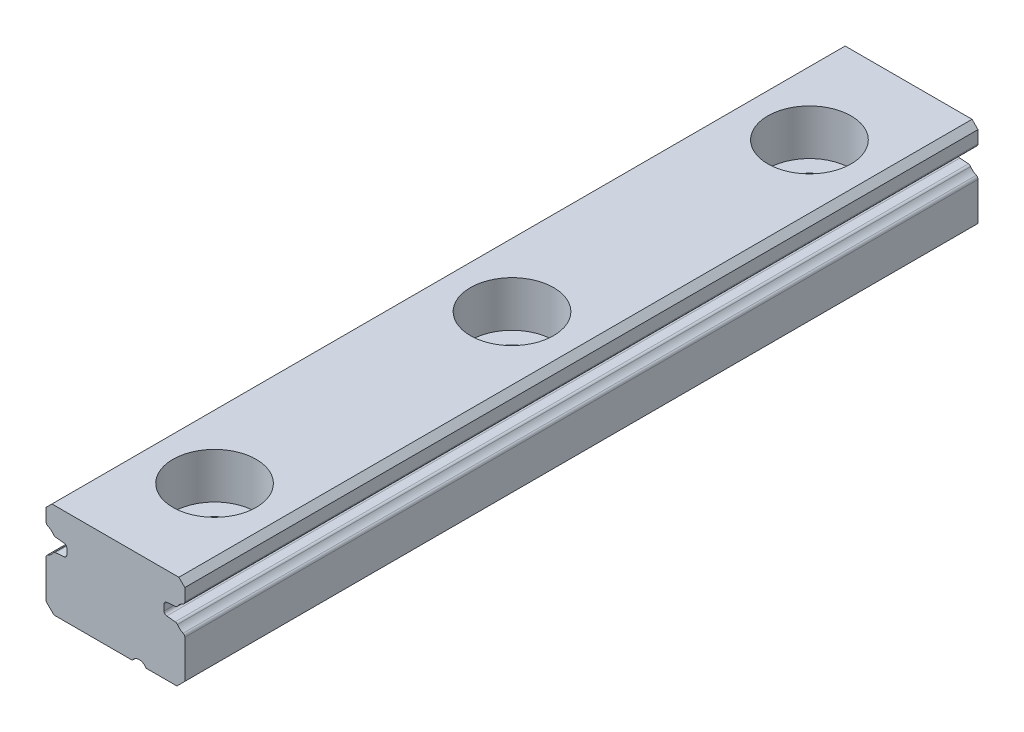
SolidWorks part; units mm, degrees
ref_plane "Front Plane" through (0, 0, 0) normal (0, 0, 1) x (1, 0, 0)
ref_plane "Top Plane" through (0, 0, 0) normal (0, 1, 0) x (1, 0, 0)
ref_plane "Right Plane" through (0, 0, 0) normal (1, 0, 0) x (0, 0, -1)
sketch "Sketch1" plane through (0, 0, 0) normal (0, 0, 1) x (1, 0, 0)
  line L0 (-3.5, 0) -> (3.5, 0) construction
  line L1 (0, -2.4) -> (0, 2.4) construction
  line L2 (0, 2.4) -> (0, -2.4) construction
  line L3 (-2.1, 2.4) -> (2.1, 2.4) construction
  line L4 (-1.2, 0.1) -> (1.2, 0.1) construction
  point P0 (0, 0.1)
  point P3 (-3.5, -2.4)
  point P4 (0, 0)
  point P8 (0, 0)
  point P11 (0, 2.4)
  point P15 (0, 2.4)
  point P17 (0, 0.1)
  point P18 (3.5, 2.4)
  point P20 (-3.5, 2.4)
  dimension "Rail Width" = 7
  dimension "Rail Height" = 4.8
  dimension "Mounting Hole Depth" = 2.5
  dimension "Mounting Hole Counterbore Diameter" = 4.2
  dimension "Mounting Hole Diameter" = 2.4
sketch "Sketch2" plane through (0, 0, 0) normal (1, 0, 0) x (0, 0, -1)
  line L0 (20, 0) -> (-20, 0) construction
  line L1 (-1.5, 2.4) -> (1.5, 2.4) construction
  line L3 (0, 2.4) -> (0, 0) construction
  point P0 (-15, 0)
  point P4 (0, 0)
  point P5 (0, 0)
  point P6 (-7.5, 0)
  point P9 (-15, 2.4)
  point P10 (0, 2.4)
  point P11 (20, 2.4)
  point P13 (-20, 2.4)
  point P14 (7.5, 0)
  point P17 (-20, -2.4)
  dimension "Rail Length" = 40
  dimension "Mounting Hole Center to Edge" = 5
  dimension "Mounting Hole Center to Center" = 15
  dimension "Number of Mounting Holes" = 3
  dimension "Break Line" = 7.5
sketch "Sketch3" plane through (0, 0, 0) normal (0, 0, 1) x (1, 0, 0)
  point P0 (0, 2.4)
  line B0 (-3.5, -0.0746) -> (-3.5, -2)
  line B1 (-3.5, -2) -> (-3.1, -2.4)
  line B2 (-3.1, -2.4) -> (0.8536, -2.4)
  line B3 (1.5464, -2.4) -> (3.1, -2.4)
  line B4 (3.1, -2.4) -> (3.5, -2)
  line B5 (3.5, -2) -> (3.5, -0.0746)
  line B6 (3.0163, 0.3626) -> (2.5869, 0.4002)
  line B7 (2.45, 0.5496) -> (2.45, 0.8504)
  line B8 (2.5869, 0.9998) -> (3.0163, 1.0374)
  line B9 (3.5, 1.4746) -> (3.5, 2.1)
  line B10 (3.5, 2.1) -> (3.2, 2.4)
  line B11 (3.2, 2.4) -> (-3.2, 2.4)
  line B12 (-3.2, 2.4) -> (-3.5, 2.1)
  line B13 (-3.5, 2.1) -> (-3.5, 1.4746)
  line B14 (-3.0163, 1.0374) -> (-2.5869, 0.9998)
  line B15 (-2.45, 0.8504) -> (-2.45, 0.5496)
  line B16 (-2.5869, 0.4002) -> (-3.0163, 0.3626)
  arc B17 (1.5464, -2.4) -> (0.8536, -2.4) centre (1.2, -2.6) ccw
  arc B18 (3.5, -0.0746) -> (3.4118, 0.0621) centre (3.35, -0.0746) ccw
  arc B19 (3.1262, 0.2991) -> (3.4118, 0.0621) centre (3.7, 0.7) ccw
  arc B20 (3.1262, 0.2991) -> (3.0163, 0.3626) centre (3.0032, 0.2132) ccw
  arc B21 (2.45, 0.5496) -> (2.5869, 0.4002) centre (2.6, 0.5496) ccw
  arc B22 (2.5869, 0.9998) -> (2.45, 0.8504) centre (2.6, 0.8504) ccw
  arc B23 (3.0163, 1.0374) -> (3.1262, 1.1009) centre (3.0032, 1.1868) ccw
  arc B24 (3.4118, 1.3379) -> (3.1262, 1.1009) centre (3.7, 0.7) ccw
  arc B25 (3.4118, 1.3379) -> (3.5, 1.4746) centre (3.35, 1.4746) ccw
  arc B26 (-3.5, 1.4746) -> (-3.4118, 1.3379) centre (-3.35, 1.4746) ccw
  arc B27 (-3.1262, 1.1009) -> (-3.4118, 1.3379) centre (-3.7, 0.7) ccw
  arc B28 (-3.1262, 1.1009) -> (-3.0163, 1.0374) centre (-3.0032, 1.1868) ccw
  arc B29 (-2.45, 0.8504) -> (-2.5869, 0.9998) centre (-2.6, 0.8504) ccw
  arc B30 (-2.5869, 0.4002) -> (-2.45, 0.5496) centre (-2.6, 0.5496) ccw
  arc B31 (-3.0163, 0.3626) -> (-3.1262, 0.2991) centre (-3.0032, 0.2132) ccw
  arc B32 (-3.4118, 0.0621) -> (-3.1262, 0.2991) centre (-3.7, 0.7) ccw
  arc B33 (-3.4118, 0.0621) -> (-3.5, -0.0746) centre (-3.35, -0.0746) ccw
sketch_block_instance "7mm Block-1"
sketch_block "7mm Block"
extrude "Boss-Extrude1" add sketch "Sketch3" against normal up to vertex (20 mm away) from vertex at 20 starting at point (0, 0, 20)
ref_plane "Plane1" through (0, 0, 15) normal (0, 0, 1) x (1, 0, 0)
sketch "Sketch4" plane through (0, 0, 15) normal (0, 0, 1) x (1, 0, 0)
  line L0 (0, 2.4) -> (0, -2.4)
  line L1 (0, -2.4) -> (-1.2, -2.4)
  line L3 (-1.2, -2.4) -> (-1.2, 0.1)
  line L4 (-1.2, 0.1) -> (-2.1, 0.1)
  line L5 (-2.1, 0.1) -> (-2.1, 2.4)
  line L6 (-2.1, 2.4) -> (0, 2.4)
revolve "Cut-Revolve1" cut sketch "Sketch4" angle 360 about L0
sketch "Sketch6" plane through (0, 0, 0) normal (1, 0, 0) x (0, 0, -1)
  line L0 (-12.9, 0.1) -> (-17.1, 0.1) construction
  line L5 (-12.9, 0.1) -> (-17.1, 0.1)
  line L17 (-16.2, 0.1) -> (-16.2, -2.4) construction
  line L18 (-13.8, -2.4) -> (-13.8, 0.1) construction
  line L32 (-12.9, 0.1) -> (-12.9, 2.4) construction
  line L33 (-17.1, 2.4) -> (-17.1, 0.1) construction
  line L34 (-16.2, 0.1) -> (-16.2, -2.4)
  line L35 (-13.8, -2.4) -> (-13.8, 0.1)
  line L36 (-12.9, 0.1) -> (-12.9, 2.4)
  line L37 (-17.1, 2.4) -> (-17.1, 0.1)
  line L38 (0, 2.4) -> (0, -2.4) construction
  line L40 (17.1, 2.4) -> (17.1, 0.1)
  line L41 (12.9, 0.1) -> (12.9, 2.4)
  line L42 (13.8, -2.4) -> (13.8, 0.1)
  line L43 (16.2, 0.1) -> (16.2, -2.4)
  line L44 (12.9, 0.1) -> (17.1, 0.1)
sketch "Sketch7" plane through (0, 0, 0) normal (0, 0, 1) x (1, 0, 0)
  line L0 (2.1, 0.1) -> (2.1, 2.4) construction
  line L1 (-2.1, 2.4) -> (-2.1, 0.1) construction
  line L2 (2.1, 0.1) -> (2.1, 2.4)
  line L3 (-2.1, 2.4) -> (-2.1, 0.1)
  line L18 (-1.2, 0.1) -> (-1.2, -2.4) construction
  line L30 (1.2, -2.2) -> (1.2, 0.1) construction
  line L32 (2.1, 0.1) -> (-2.1, 0.1) construction
  line L34 (-1.2, 0.1) -> (-1.2, -2.4)
  line L35 (1.2, -2.2) -> (1.2, 0.1)
  line L37 (2.1, 0.1) -> (-2.1, 0.1)
pattern_linear "LPattern1" count 3 spacing 15 along (0, 0, -1) of "Cut-Revolve1"
equation "\"D3@LPattern1\"=\"Mounting Hole Center to Center@Sketch2\""
equation "\"D1@LPattern1\"=\"Number of Mounting Holes@Sketch2\""
equation "\"Break Line@Sketch2\"=\"Mounting Hole Center to Center@Sketch2\"/2"
